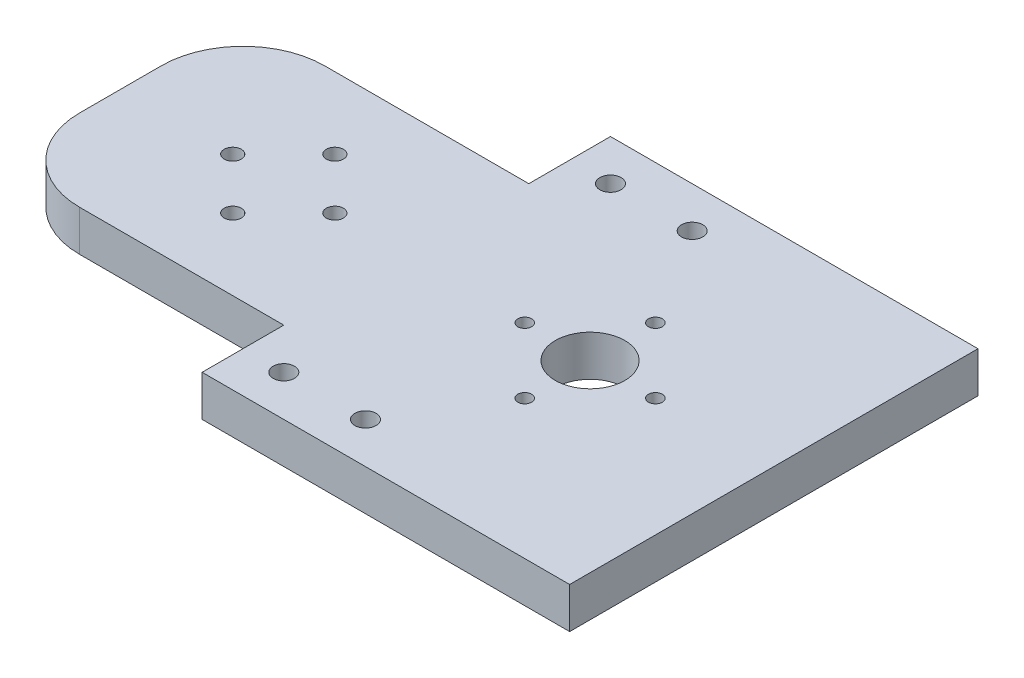
SolidWorks part; units mm, degrees
ref_plane "前视基准面" through (0, 0, 0) normal (0, 0, 1) x (1, 0, 0)
ref_plane "上视基准面" through (0, 0, 0) normal (0, 1, 0) x (1, 0, 0)
ref_plane "右视基准面" through (0, 0, 0) normal (1, 0, 0) x (0, 0, -1)
other "Configuration Table"
sketch "草图2" plane through (0, 0, 0) normal (0, 1, 0) x (1, 0, 0)
  line L0 (0, 50) -> (0, -50)
  line L1 (0, -50) -> (-90, -50)
  line L2 (-90, -50) -> (-90, -30)
  line L3 (-90, -30) -> (-160, -30)
  line L4 (-160, -30) -> (-160, 30)
  line L5 (-160, 30) -> (-90, 30)
  line L6 (-90, 30) -> (-90, 50)
  line L7 (-90, 50) -> (0, 50)
  dimension "D1" = 100
  dimension "D2" = 90
  dimension "D3" = 90
  dimension "D4" = 160
  dimension "D5" = 20
  dimension "D6" = 20
extrude "凸台-拉伸2" add sketch "草图2" along normal blind 10
fillet "圆角2" radius 20 2 edges at (-160, 5, 30) (-160, 5, -30)
sketch "草图4" plane through (0, 10, 0) normal (0, 1, 0) x (1, 0, 0)
  circle A0 centre (-60, -40) radius 2.6
  circle A1 centre (-80, -40) radius 2.6
  circle A2 centre (-80, 40) radius 2.6
  circle A3 centre (-60, 40) radius 2.6
  dimension "D1" = 5.2
  dimension "D2" = 5.2
  dimension "D3" = 5.2
  dimension "D4" = 5.2
extrude "切除-拉伸2" cut sketch "草图4" against normal through all
cosmetic thread "装饰螺纹线17" parameters "D2"=6.2
cosmetic thread "装饰螺纹线18" parameters "D2"=6.2
cosmetic thread "装饰螺纹线19" parameters "D2"=6.2
cosmetic thread "装饰螺纹线20" parameters "D2"=6.2
sketch "草图5" plane through (0, 0, 0) normal (0, -1, 0) x (1, 0, 0)
  circle A0 centre (-45, 0) radius 8.5
  dimension "D1" = 17
extrude "切除-拉伸3" cut sketch "草图5" against normal through all
sketch "草图17" plane through (0, 0, 0) normal (0, -1, 0) x (1, 0, 0)
  line L0 (-45, 0) -> (-45, -50) construction
  line L1 (0, -50) -> (-90, -50) construction
  line L2 (-45, 0) -> (-45, 50) construction
  line L3 (-90, 50) -> (0, 50) construction
  line L4 (0, 0) -> (-160, 0) construction
  line L5 (-160, -10) -> (-160, 10) construction
  circle A0 centre (-45, 16) radius 1.7
  circle A1 centre (-45, -16) radius 1.7
  circle A2 centre (-45, 0) radius 8.5 construction
  circle A3 centre (-29, 0) radius 1.7
  circle A4 centre (-61, 0) radius 1.7
  dimension "D1" = 3.4
  dimension "D2" = 3.4
  dimension "D3" = 16
  dimension "D4" = 16
  dimension "D5" = 3.4
  dimension "D6" = 16
extrude "切除-拉伸11" cut sketch "草图17" against normal blind 10
cosmetic thread "装饰螺纹线13" parameters "D2"=4.4
cosmetic thread "装饰螺纹线14" parameters "D2"=4.4
cosmetic thread "装饰螺纹线15" parameters "D2"=4.4
cosmetic thread "装饰螺纹线16" parameters "D2"=4.4
sketch "草图18" plane through (0, 0, 0) normal (0, -1, 0) x (1, 0, 0)
  line L0 (-160, -10) -> (-160, 10) construction
  circle A0 centre (-120, 0) radius 12.5 construction
  circle A1 centre (-120, 12.5) radius 2.1
  circle A2 centre (-132.5, 0) radius 2.1
  circle A3 centre (-120, -12.5) radius 2.1
  circle A4 centre (-107.5, 0) radius 2.1
  dimension "D1" = 25
  dimension "D2" = 40
  dimension "D3" = 4.2
  dimension "D4" = 4.2
  dimension "D5" = 4.2
  dimension "D6" = 4.2
extrude "切除-拉伸12" cut sketch "草图18" against normal blind 10
cosmetic thread "装饰螺纹线21" parameters "D2"=5.2
cosmetic thread "装饰螺纹线22" parameters "D2"=5.2
cosmetic thread "装饰螺纹线23" parameters "D2"=5.2
cosmetic thread "装饰螺纹线24" parameters "D2"=5.2
